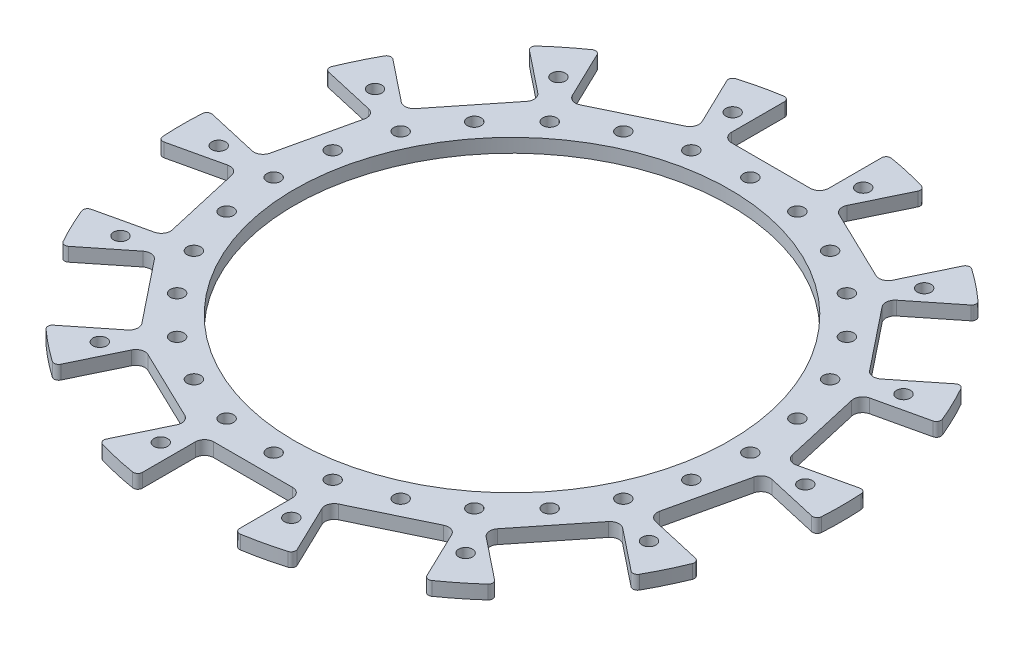
SolidWorks part; units mm, degrees
material "Thornel Mat VMA"
ref_plane "前视基准面" through (0, 0, 0) normal (0, 0, 1) x (1, 0, 0)
ref_plane "上视基准面" through (0, 0, 0) normal (0, 1, 0) x (1, 0, 0)
ref_plane "右视基准面" through (0, 0, 0) normal (1, 0, 0) x (0, 0, -1)
sketch "草图1" plane through (0, 0, 0) normal (0, 1, 0) x (1, 0, 0)
  line L0 (0, 0) -> (0, -67) construction
  line L1 (13, -67) -> (-13, -67) construction
  line L2 (-13, -68.5) -> (-13, -65.5)
  line L3 (0, -67) -> (0, -69.5129) construction
  line L4 (-10.1, -69.5129) -> (10.1, -69.5129) construction
  line L5 (-13, -68.5) -> (-10.6, -68.5)
  line L6 (-10.6, -68.5) -> (-10.6, -71.2154)
  line L7 (-13, -65.5) -> (-10.6, -65.5)
  line L8 (-10.6, -65.5) -> (-10.6, -56.5)
  line L9 (-10.6, -56.5) -> (10.6, -56.5)
  line L10 (10.6, -68.5) -> (10.6, -71.2154)
  line L11 (13, -68.5) -> (10.6, -68.5)
  line L12 (13, -68.5) -> (13, -65.5)
  line L13 (13, -65.5) -> (10.6, -65.5)
  line L14 (10.6, -65.5) -> (10.6, -56.5)
  line L15 (-34.0647, -46.3056) -> (-14.9642, -55.5039)
  line L16 (-37.9697, -54.4143) -> (-34.0647, -46.3056)
  line L17 (-40.132, -53.373) -> (-37.9697, -54.4143)
  line L18 (-41.4336, -56.0759) -> (-40.132, -53.373)
  line L19 (-41.4336, -56.0759) -> (-39.2713, -57.1172)
  line L20 (-39.2713, -57.1172) -> (-40.4495, -59.5637)
  line L21 (-20.1708, -66.3155) -> (-21.349, -68.7621)
  line L22 (-18.0084, -67.3569) -> (-20.1708, -66.3155)
  line L23 (-18.0084, -67.3569) -> (-16.7068, -64.6539)
  line L24 (-16.7068, -64.6539) -> (-18.8691, -63.6126)
  line L25 (-18.8691, -63.6126) -> (-14.9642, -55.5039)
  line L26 (-50.7825, -26.9398) -> (-37.5645, -43.5146)
  line L27 (-57.819, -32.5512) -> (-50.7825, -26.9398)
  line L28 (-59.3153, -30.6748) -> (-57.819, -32.5512)
  line L29 (-61.6608, -32.5452) -> (-59.3153, -30.6748)
  line L30 (-61.6608, -32.5452) -> (-60.1644, -34.4216)
  line L31 (-60.1644, -34.4216) -> (-62.2875, -36.1147)
  line L32 (-46.9465, -50.9965) -> (-49.0695, -52.6895)
  line L33 (-45.4501, -52.8729) -> (-46.9465, -50.9965)
  line L34 (-45.4501, -52.8729) -> (-43.1046, -51.0024)
  line L35 (-43.1046, -51.0024) -> (-44.601, -49.126)
  line L36 (-44.601, -49.126) -> (-37.5645, -43.5146)
  line L37 (-57.4421, -2.2382) -> (-52.7247, -22.9067)
  line L38 (-66.2165, -4.2409) -> (-57.4421, -2.2382)
  line L39 (-66.7506, -1.9011) -> (-66.2165, -4.2409)
  line L40 (-69.6753, -2.5686) -> (-66.7506, -1.9011)
  line L41 (-69.6753, -2.5686) -> (-69.1413, -4.9084)
  line L42 (-69.1413, -4.9084) -> (-71.7886, -5.5127)
  line L43 (-64.4238, -25.5769) -> (-67.0712, -26.1812)
  line L44 (-63.8898, -27.9167) -> (-64.4238, -25.5769)
  line L45 (-63.8898, -27.9167) -> (-60.965, -27.2492)
  line L46 (-60.965, -27.2492) -> (-61.4991, -24.9094)
  line L47 (-61.4991, -24.9094) -> (-52.7247, -22.9067)
  line L48 (-52.7247, 22.9067) -> (-57.4421, 2.2382)
  line L49 (-61.4991, 24.9094) -> (-52.7247, 22.9067)
  line L50 (-60.965, 27.2492) -> (-61.4991, 24.9094)
  line L51 (-63.8898, 27.9167) -> (-60.965, 27.2492)
  line L52 (-63.8898, 27.9167) -> (-64.4238, 25.5769)
  line L53 (-64.4238, 25.5769) -> (-67.0712, 26.1812)
  line L54 (-69.1413, 4.9084) -> (-71.7886, 5.5127)
  line L55 (-69.6753, 2.5686) -> (-69.1413, 4.9084)
  line L56 (-69.6753, 2.5686) -> (-66.7506, 1.9011)
  line L57 (-66.7506, 1.9011) -> (-66.2165, 4.2409)
  line L58 (-66.2165, 4.2409) -> (-57.4421, 2.2382)
  line L59 (-37.5645, 43.5146) -> (-50.7825, 26.9398)
  line L60 (-44.601, 49.126) -> (-37.5645, 43.5146)
  line L61 (-43.1046, 51.0024) -> (-44.601, 49.126)
  line L62 (-45.4501, 52.8729) -> (-43.1046, 51.0024)
  line L63 (-45.4501, 52.8729) -> (-46.9465, 50.9965)
  line L64 (-46.9465, 50.9965) -> (-49.0695, 52.6895)
  line L65 (-60.1644, 34.4216) -> (-62.2875, 36.1147)
  line L66 (-61.6608, 32.5452) -> (-60.1644, 34.4216)
  line L67 (-61.6608, 32.5452) -> (-59.3153, 30.6748)
  line L68 (-59.3153, 30.6748) -> (-57.819, 32.5512)
  line L69 (-57.819, 32.5512) -> (-50.7825, 26.9398)
  line L70 (-14.9642, 55.5039) -> (-34.0647, 46.3056)
  line L71 (-18.8691, 63.6126) -> (-14.9642, 55.5039)
  line L72 (-16.7068, 64.6539) -> (-18.8691, 63.6126)
  line L73 (-18.0084, 67.3569) -> (-16.7068, 64.6539)
  line L74 (-18.0084, 67.3569) -> (-20.1708, 66.3155)
  line L75 (-20.1708, 66.3155) -> (-21.349, 68.7621)
  line L76 (-39.2713, 57.1172) -> (-40.4495, 59.5637)
  line L77 (-41.4336, 56.0759) -> (-39.2713, 57.1172)
  line L78 (-41.4336, 56.0759) -> (-40.132, 53.373)
  line L79 (-40.132, 53.373) -> (-37.9697, 54.4143)
  line L80 (-37.9697, 54.4143) -> (-34.0647, 46.3056)
  line L81 (10.6, 56.5) -> (-10.6, 56.5)
  line L82 (10.6, 65.5) -> (10.6, 56.5)
  line L83 (13, 65.5) -> (10.6, 65.5)
  line L84 (13, 68.5) -> (13, 65.5)
  line L85 (13, 68.5) -> (10.6, 68.5)
  line L86 (10.6, 68.5) -> (10.6, 71.2154)
  line L87 (-10.6, 68.5) -> (-10.6, 71.2154)
  line L88 (-13, 68.5) -> (-10.6, 68.5)
  line L89 (-13, 68.5) -> (-13, 65.5)
  line L90 (-13, 65.5) -> (-10.6, 65.5)
  line L91 (-10.6, 65.5) -> (-10.6, 56.5)
  line L92 (34.0647, 46.3056) -> (14.9642, 55.5039)
  line L93 (37.9697, 54.4143) -> (34.0647, 46.3056)
  line L94 (40.132, 53.373) -> (37.9697, 54.4143)
  line L95 (41.4336, 56.0759) -> (40.132, 53.373)
  line L96 (41.4336, 56.0759) -> (39.2713, 57.1172)
  line L97 (39.2713, 57.1172) -> (40.4495, 59.5637)
  line L98 (20.1708, 66.3155) -> (21.349, 68.7621)
  line L99 (18.0084, 67.3569) -> (20.1708, 66.3155)
  line L100 (18.0084, 67.3569) -> (16.7068, 64.6539)
  line L101 (16.7068, 64.6539) -> (18.8691, 63.6126)
  line L102 (18.8691, 63.6126) -> (14.9642, 55.5039)
  line L103 (50.7825, 26.9398) -> (37.5645, 43.5146)
  line L104 (57.819, 32.5512) -> (50.7825, 26.9398)
  line L105 (59.3153, 30.6748) -> (57.819, 32.5512)
  line L106 (61.6608, 32.5452) -> (59.3153, 30.6748)
  line L107 (61.6608, 32.5452) -> (60.1644, 34.4216)
  line L108 (60.1644, 34.4216) -> (62.2875, 36.1147)
  line L109 (46.9465, 50.9965) -> (49.0695, 52.6895)
  line L110 (45.4501, 52.8729) -> (46.9465, 50.9965)
  line L111 (45.4501, 52.8729) -> (43.1046, 51.0024)
  line L112 (43.1046, 51.0024) -> (44.601, 49.126)
  line L113 (44.601, 49.126) -> (37.5645, 43.5146)
  line L114 (57.4421, 2.2382) -> (52.7247, 22.9067)
  line L115 (66.2165, 4.2409) -> (57.4421, 2.2382)
  line L116 (66.7506, 1.9011) -> (66.2165, 4.2409)
  line L117 (69.6753, 2.5686) -> (66.7506, 1.9011)
  line L118 (69.6753, 2.5686) -> (69.1413, 4.9084)
  line L119 (69.1413, 4.9084) -> (71.7886, 5.5127)
  line L120 (64.4238, 25.5769) -> (67.0712, 26.1812)
  line L121 (63.8898, 27.9167) -> (64.4238, 25.5769)
  line L122 (63.8898, 27.9167) -> (60.965, 27.2492)
  line L123 (60.965, 27.2492) -> (61.4991, 24.9094)
  line L124 (61.4991, 24.9094) -> (52.7247, 22.9067)
  line L125 (52.7247, -22.9067) -> (57.4421, -2.2382)
  line L126 (61.4991, -24.9094) -> (52.7247, -22.9067)
  line L127 (60.965, -27.2492) -> (61.4991, -24.9094)
  line L128 (63.8898, -27.9167) -> (60.965, -27.2492)
  line L129 (63.8898, -27.9167) -> (64.4238, -25.5769)
  line L130 (64.4238, -25.5769) -> (67.0712, -26.1812)
  line L131 (69.1413, -4.9084) -> (71.7886, -5.5127)
  line L132 (69.6753, -2.5686) -> (69.1413, -4.9084)
  line L133 (69.6753, -2.5686) -> (66.7506, -1.9011)
  line L134 (66.7506, -1.9011) -> (66.2165, -4.2409)
  line L135 (66.2165, -4.2409) -> (57.4421, -2.2382)
  line L136 (37.5645, -43.5146) -> (50.7825, -26.9398)
  line L137 (44.601, -49.126) -> (37.5645, -43.5146)
  line L138 (43.1046, -51.0024) -> (44.601, -49.126)
  line L139 (45.4501, -52.8729) -> (43.1046, -51.0024)
  line L140 (45.4501, -52.8729) -> (46.9465, -50.9965)
  line L141 (46.9465, -50.9965) -> (49.0695, -52.6895)
  line L142 (60.1644, -34.4216) -> (62.2875, -36.1147)
  line L143 (61.6608, -32.5452) -> (60.1644, -34.4216)
  line L144 (61.6608, -32.5452) -> (59.3153, -30.6748)
  line L145 (59.3153, -30.6748) -> (57.819, -32.5512)
  line L146 (57.819, -32.5512) -> (50.7825, -26.9398)
  line L147 (14.9642, -55.5039) -> (34.0647, -46.3056)
  line L148 (18.8691, -63.6126) -> (14.9642, -55.5039)
  line L149 (16.7068, -64.6539) -> (18.8691, -63.6126)
  line L150 (18.0084, -67.3569) -> (16.7068, -64.6539)
  line L151 (18.0084, -67.3569) -> (20.1708, -66.3155)
  line L152 (20.1708, -66.3155) -> (21.349, -68.7621)
  line L153 (39.2713, -57.1172) -> (40.4495, -59.5637)
  line L154 (41.4336, -56.0759) -> (39.2713, -57.1172)
  line L155 (41.4336, -56.0759) -> (40.132, -53.373)
  line L156 (40.132, -53.373) -> (37.9697, -54.4143)
  line L157 (37.9697, -54.4143) -> (34.0647, -46.3056)
  line L158 (-10.6, -65.5) -> (-10.6, -68.5)
  line L159 (10.6, -65.5) -> (10.6, -68.5)
  line L160 (-18.8691, -63.6126) -> (-20.1708, -66.3155)
  line L161 (-37.9697, -54.4143) -> (-39.2713, -57.1172)
  line L162 (-44.601, -49.126) -> (-46.9465, -50.9965)
  line L163 (-57.819, -32.5512) -> (-60.1644, -34.4216)
  line L164 (-61.4991, -24.9094) -> (-64.4238, -25.5769)
  line L165 (-66.2165, -4.2409) -> (-69.1413, -4.9084)
  line L166 (-66.2165, 4.2409) -> (-69.1413, 4.9084)
  line L167 (-61.4991, 24.9094) -> (-64.4238, 25.5769)
  line L168 (-57.819, 32.5512) -> (-60.1644, 34.4216)
  line L169 (-44.601, 49.126) -> (-46.9465, 50.9965)
  line L170 (-37.9697, 54.4143) -> (-39.2713, 57.1172)
  line L171 (-18.8691, 63.6126) -> (-20.1708, 66.3155)
  line L172 (-10.6, 65.5) -> (-10.6, 68.5)
  line L173 (10.6, 65.5) -> (10.6, 68.5)
  line L174 (18.8691, 63.6126) -> (20.1708, 66.3155)
  line L175 (37.9697, 54.4143) -> (39.2713, 57.1172)
  line L176 (44.601, 49.126) -> (46.9465, 50.9965)
  line L177 (57.819, 32.5512) -> (60.1644, 34.4216)
  line L178 (61.4991, 24.9094) -> (64.4238, 25.5769)
  line L179 (66.2165, 4.2409) -> (69.1413, 4.9084)
  line L180 (66.2165, -4.2409) -> (69.1413, -4.9084)
  line L181 (61.4991, -24.9094) -> (64.4238, -25.5769)
  line L182 (57.819, -32.5512) -> (60.1644, -34.4216)
  line L183 (44.601, -49.126) -> (46.9465, -50.9965)
  line L184 (37.9697, -54.4143) -> (39.2713, -57.1172)
  line L185 (18.8691, -63.6126) -> (20.1708, -66.3155)
  circle A0 centre (0, 0) radius 67 construction
  circle A1 centre (0, 0) radius 72
  point P7 (0, -67)
  point P10 (-13, -67)
  point P21 (0, -69.5129)
  point P26 (0, -56.5)
  point P185 (0, 0)
  point P237 (0, 0)
  dimension "D1" = 134
  dimension "D5" = 144
  dimension "D2" = 26
  dimension "D3" = 3
  dimension "D4" = 20.2
  dimension "D6" = 0.5
  dimension "D7" = 10.5
  dimension "D8" = 14
  dimension "D9" = 14
extrude "凸台-拉伸1" add sketch "草图1" along normal blind 3 contours L10 A1 L152 L151 L150 L149 L148 L147 L157 L156 L155 L154 L153 L141 L140 L139 L138 L137 L136 L146 L145 L144 L143 L142 L130 L129 L128 L127 L126 L125 L135 L134 L133 L132 L131 L119 L118 L117 L116 L115 L114 L124 L123 L122 L121 L120 L108 | L161 L17 L18 L19 | L163 L28 L29 L30 | L35 L162 L33 L34 | L46 L164 L44 L45 | L24 L160 L22 L23 | L158 L7 L2 L5 | L185 L149 L150 L151 | L13 L159 L11 L12 | L156 L184 L154 L155 | L183 L138 L139 L140 | L145 L182 L143 L144 | L181 L127 L128 L129 | L134 L180 L132 L133 | L179 L116 L117 L118 | L177 L105 L106 L107 | L123 L178 L121 L122 | L112 L176 L110 L111 | L175 L94 L95 L96 | L101 L174 L99 L100 | L173 L83 L84 L85 | L171 L72 L73 L74 | L90 L172 L88 L89 | L169 L61 L62 L63 | L79 L170 L77 L78 | L167 L50 L51 L52 | L68 L168 L66 L67 | L165 L39 L40 L41 | L57 L166 L55 L56
fillet "圆角1" radius 2 28 edges at (50.7825, 1.5, 26.9398) (57.4421, 1.5, 2.2382) (52.7247, 1.5, -22.9067) (37.5645, 1.5, -43.5146) (14.9642, 1.5, -55.5039) (-10.6, 1.5, -56.5) (-34.0647, 1.5, -46.3056) (-50.7825, 1.5, -26.9398) (-57.4421, 1.5, -2.2382) (-52.7247, 1.5, 22.9067) (-37.5645, 1.5, 43.5146) (-14.9642, 1.5, 55.5039) (-34.0647, 1.5, 46.3056) (-50.7825, 1.5, 26.9398) (-57.4421, 1.5, 2.2382) (-52.7247, 1.5, -22.9067) (-37.5645, 1.5, -43.5146) (-14.9642, 1.5, -55.5039) (10.6, 1.5, -56.5) (34.0647, 1.5, -46.3056) (57.4421, 1.5, -2.2382) (50.7825, 1.5, -26.9398) (52.7247, 1.5, 22.9067) (37.5645, 1.5, 43.5146) (34.0647, 1.5, 46.3056) (14.9642, 1.5, 55.5039) (10.6, 1.5, 56.5) (-10.6, 1.5, 56.5)
fillet "圆角2" radius 1 28 edges at (40.4495, 1.5, 59.5637) (10.6, 1.5, 71.2154) (62.2875, 1.5, 36.1147) (71.7886, 1.5, 5.5127) (67.0712, 1.5, -26.1812) (49.0695, 1.5, -52.6895) (21.349, 1.5, -68.7621) (-10.6, 1.5, -71.2154) (-40.4495, 1.5, -59.5637) (-62.2875, 1.5, -36.1147) (-71.7886, 1.5, -5.5127) (-67.0712, 1.5, 26.1812) (71.7886, 1.5, -5.5127) (-21.349, 1.5, 68.7621) (40.4495, 1.5, -59.5637) (-49.0695, 1.5, 52.6895) (62.2875, 1.5, -36.1147) (-40.4495, 1.5, 59.5637) (-62.2875, 1.5, 36.1147) (-71.7886, 1.5, 5.5127) (-67.0712, 1.5, -26.1812) (-49.0695, 1.5, -52.6895) (-21.349, 1.5, -68.7621) (10.6, 1.5, -71.2154) (67.0712, 1.5, 26.1812) (49.0695, 1.5, 52.6895) (21.349, 1.5, 68.7621) (-10.6, 1.5, 71.2154)
sketch "草图2" plane through (0, 0, 0) normal (0, 1, 0) x (1, 0, 0)
  line L0 (64, 0) -> (0, 0) construction
  circle A0 centre (64, 0) radius 1.5
  circle A1 centre (57.662, -27.7686) radius 1.5
  circle A2 centre (39.9033, -50.0372) radius 1.5
  circle A3 centre (14.2413, -62.3954) radius 1.5
  circle A4 centre (-14.2413, -62.3954) radius 1.5
  circle A5 centre (-39.9033, -50.0372) radius 1.5
  circle A6 centre (-57.662, -27.7686) radius 1.5
  circle A7 centre (-64, 0) radius 1.5
  circle A8 centre (-57.662, 27.7686) radius 1.5
  circle A9 centre (-39.9033, 50.0372) radius 1.5
  circle A10 centre (-14.2413, 62.3954) radius 1.5
  circle A11 centre (14.2413, 62.3954) radius 1.5
  circle A12 centre (39.9033, 50.0372) radius 1.5
  circle A13 centre (57.662, 27.7686) radius 1.5
  point P32 (0, 0)
  dimension "D1" = 3
  dimension "D2" = 64
  dimension "D3" = 14
extrude "切除-拉伸1" cut sketch "草图2" along normal blind 11
sketch "草图3" plane through (0, 0, 0) normal (0, 1, 0) x (1, 0, 0)
  line L0 (0, -56.5) -> (0, -52.5) construction
  line L1 (-8.6, -56.5) -> (8.6, -56.5) construction
  circle A0 centre (0, 0) radius 9
  circle A1 centre (0, 0) radius 28
  circle A2 centre (0, 0) radius 52.5
  dimension "D1" = 18
  dimension "D2" = 56
  dimension "D3" = 4
extrude "切除-拉伸2" cut sketch "草图3" along normal blind 11 contours A0 | A2 A1 | A1 A0
sketch "草图9" plane through (0, 3, 0) normal (0, 1, 0) x (1, 0, 0)
  circle A0 centre (0, 0) radius 52.5
  circle A1 centre (0, 0) radius 47.5
  dimension "D1" = 105
  dimension "D2" = 95
extrude "凸台-拉伸2" add sketch "草图9" against normal blind 3
sketch "草图10" plane through (0, 3, 0) normal (0, 1, 0) x (1, 0, 0)
  circle A0 centre (0, 0) radius 52 construction
  circle A1 centre (0, 52) radius 1.5
  circle A2 centre (11.5711, 50.6963) radius 1.5
  circle A3 centre (22.562, 46.8504) radius 1.5
  circle A4 centre (32.4215, 40.6552) radius 1.5
  circle A5 centre (40.6552, 32.4215) radius 1.5
  circle A6 centre (46.8504, 22.562) radius 1.5
  circle A7 centre (50.6963, 11.5711) radius 1.5
  circle A8 centre (52, 0) radius 1.5
  circle A9 centre (50.6963, -11.5711) radius 1.5
  circle A10 centre (46.8504, -22.562) radius 1.5
  circle A11 centre (40.6552, -32.4215) radius 1.5
  circle A12 centre (32.4215, -40.6552) radius 1.5
  circle A13 centre (22.562, -46.8504) radius 1.5
  circle A14 centre (11.5711, -50.6963) radius 1.5
  circle A15 centre (0, -52) radius 1.5
  circle A16 centre (-11.5711, -50.6963) radius 1.5
  circle A17 centre (-22.562, -46.8504) radius 1.5
  circle A18 centre (-32.4215, -40.6552) radius 1.5
  circle A19 centre (-40.6552, -32.4215) radius 1.5
  circle A20 centre (-46.8504, -22.562) radius 1.5
  circle A21 centre (-50.6963, -11.5711) radius 1.5
  circle A22 centre (-52, 0) radius 1.5
  circle A23 centre (-50.6963, 11.5711) radius 1.5
  circle A24 centre (-46.8504, 22.562) radius 1.5
  circle A25 centre (-40.6552, 32.4215) radius 1.5
  circle A26 centre (-32.4215, 40.6552) radius 1.5
  circle A27 centre (-22.562, 46.8504) radius 1.5
  circle A28 centre (-11.5711, 50.6963) radius 1.5
  point P62 (0, 0)
  dimension "D1" = 104
  dimension "D2" = 3
  dimension "D3" = 28
extrude "切除-拉伸3" cut sketch "草图10" against normal blind 3
